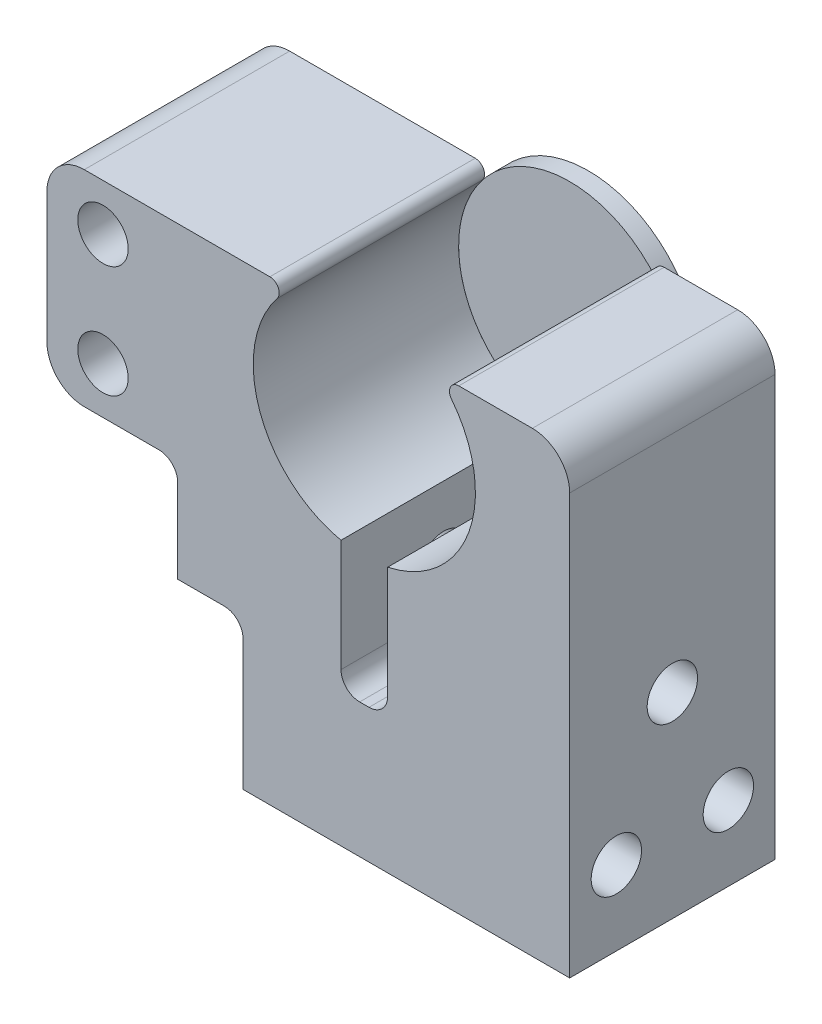
SolidWorks part; units mm, degrees
material "POM"
ref_plane "前视基准面" through (0, 0, 0) normal (0, 0, 1) x (1, 0, 0)
ref_plane "上视基准面" through (0, 0, 0) normal (0, 1, 0) x (1, 0, 0)
ref_plane "右视基准面" through (0, 0, 0) normal (1, 0, 0) x (0, 0, -1)
sketch "草图1" plane through (0, 0, 0) normal (0, 0, 1) x (1, 0, 0)
  line L0 (10, 29.3509) -> (10, -3.1119) construction
  line L1 (0, 0) -> (21, 0)
  line L5 (10, 20) -> (10, -3.1119) construction
  line L6 (0, 0) -> (0, 13.5)
  line L7 (0, 24.5) -> (6.1074, 24.5)
  line L8 (21, 24.5) -> (13.8926, 24.5)
  line L10 (21, 0) -> (21, 24.5)
  line L11 (6.1074, 24.5) -> (13.8926, 24.5) construction
  line L12 (0, 24.5) -> (-7, 24.5)
  line L13 (-7, 24.5) -> (-7, 13.5)
  line L14 (-7, 13.5) -> (0, 13.5)
  arc A1 (6.1074, 24.5) -> (13.8926, 24.5) centre (10, 20) ccw
  dimension "D4" = 11.9
  dimension "D5" = 10
  dimension "D1" = 20
  dimension "D2" = 21
  dimension "D3" = 4.5
  dimension "D6" = 11
  dimension "D7" = 7
extrude "凸台-拉伸1" add sketch "草图1" along normal blind 11
sketch "草图6" plane through (0, 0, 11) normal (0, 0, 1) x (1, 0, 0)
  line L0 (10, 20) -> (10, -1.7237) construction
  line L2 (8.75, 7.1828) -> (11.25, 7.1828)
  line L3 (8.75, 7.1828) -> (8.75, 14.1828)
  line L4 (8.75, 14.1828) -> (11.25, 14.1828)
  line L5 (11.25, 7.1828) -> (11.25, 14.1828)
  line L6 (8.75, 7.1828) -> (11.25, 14.1828) construction
  line L7 (8.75, 14.1828) -> (11.25, 7.1828) construction
  arc A0 (6.1074, 24.5) -> (13.8926, 24.5) centre (10, 20) ccw construction
  point P3 (10, 10.6828)
  dimension "D1" = 2.5
  dimension "D2" = 7
extrude "切除-拉伸2" cut sketch "草图6" against normal through all
sketch "草图2" plane through (0, 0, 0) normal (-1, 0, 0) x (0, 0, 1)
  line L0 (5.5, 0) -> (5.5, 24.5) construction
  line L1 (11, 0) -> (0, 0) construction
  line L2 (11, 24.5) -> (0, 24.5) construction
  line L3 (0, 24.5) -> (0, 14.1828) construction
  line L4 (0, 24.5) -> (0, 14.1828) construction
  line L5 (1.6433, 10.5) -> (23.7072, 10.5) construction
  line L6 (8.5, 4) -> (2.5, 4) construction
  line L7 (11, 0) -> (0, 0) construction
  line L8 (11, 24.5) -> (0, 24.5) construction
  circle A0 centre (5.5, 10.5) radius 1.35
  circle A1 centre (8.5, 4) radius 1.35
  circle A2 centre (2.5, 4) radius 1.35
  point P17 (5.5, 4)
  dimension "D2" = 2.7
  dimension "D3" = 2.7
  dimension "D1" = 14
  dimension "D4" = 6
  dimension "D5" = 4
extrude "切除-拉伸1" cut sketch "草图2" against normal through all
sketch "草图9" plane through (0, 0, 0) normal (0, 0, -1) x (-1, 0, 0)
  line L0 (1.5, 24.5) -> (1.5, 13.5) construction
  line L1 (-6.1074, 24.5) -> (7, 24.5) construction
  line L2 (7, 13.5) -> (0, 13.5) construction
  line L3 (0, 13.5) -> (0, 0) construction
  line L4 (4, 24.5) -> (4, 13.5) construction
  line L5 (4, 19) -> (7, 19) construction
  line L7 (7, 24.5) -> (7, 13.5) construction
  circle A0 centre (4, 22) radius 1.35
  circle A1 centre (4, 16) radius 1.35
  dimension "D3" = 2.7
  dimension "D4" = 6
  dimension "D1" = 1.5
  dimension "D2" = 2.5
extrude "切除-拉伸3" cut sketch "草图9" against normal through all
sketch "草图7" plane through (0, 0, 0) normal (0, 0, -1) x (-1, 0, 0)
  circle A0 centre (-10, 20) radius 5.95
  dimension "D1" = 11.9
extrude "凸台-拉伸3" add sketch "草图7" along normal blind 1 separate body
sketch "草图10" plane through (0, 0, 0) normal (-1, 0, 0) x (0, 0, 1)
  line L0 (11, 13.5) -> (11, 0) construction
  line L1 (0, 0) -> (11, 0)
  line L2 (0, 0) -> (0, 8)
  line L3 (0, 8) -> (11, 8)
  line L4 (11, 0) -> (11, 8)
  line L5 (11, 4) -> (8.5, 4) construction
extrude "切除-拉伸4" cut sketch "草图10" against normal blind 3.5
fillet "圆角2" radius 0.5 2 edges at (13.8926, 24.5, 5.5) (6.1074, 24.5, 5.5)
fillet "圆角1" radius 2 3 edges at (21, 24.5, 5.5) (-7, 13.5, 5.5) (-7, 24.5, 5.5)
fillet "圆角3" radius 1 4 edges at (0, 13.5, 5.5) (11.25, 7.1828, 5.5) (8.75, 7.1828, 5.5) (3.5, 8, 5.5)
